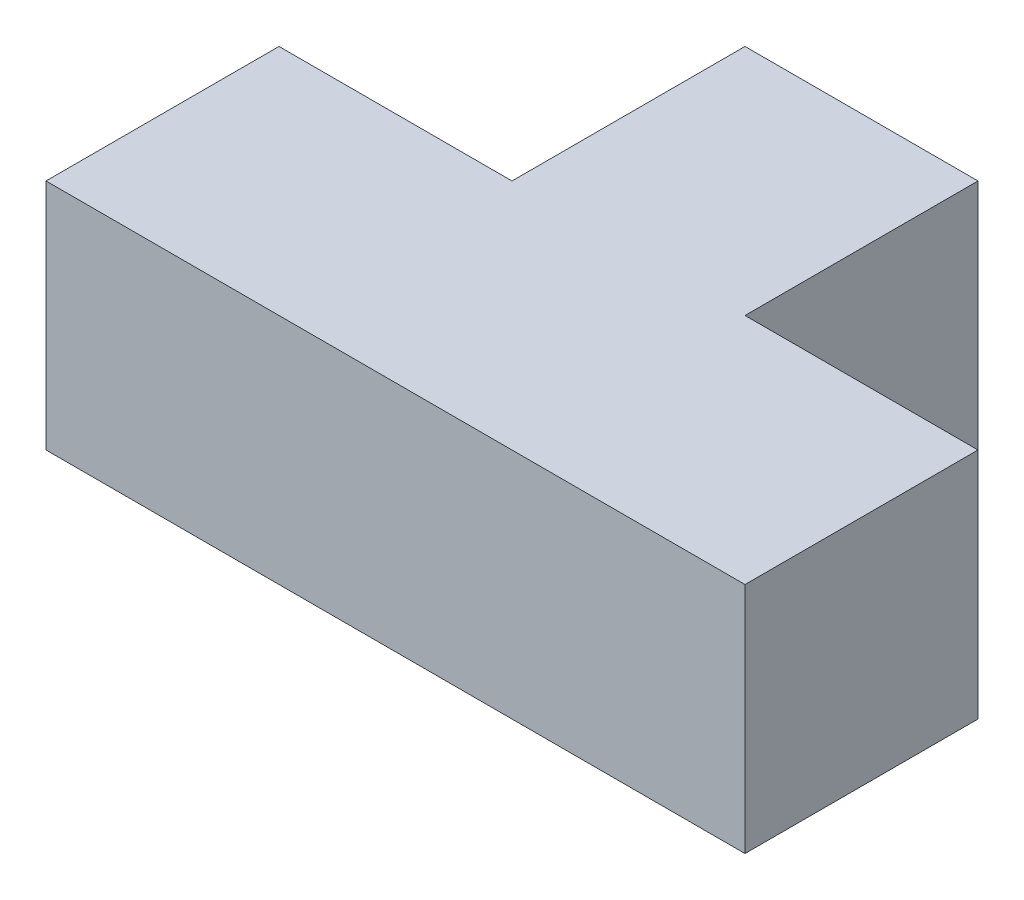
SolidWorks part; units mm, degrees
material "Oak"
ref_plane "Front Plane" through (0, 0, 0) normal (0, 0, 1) x (1, 0, 0)
ref_plane "Top Plane" through (0, 0, 0) normal (0, 1, 0) x (1, 0, 0)
ref_plane "Right Plane" through (0, 0, 0) normal (1, 0, 0) x (0, 0, -1)
sketch "Sketch1" plane through (0, 0, 0) normal (0, 1, 0) x (1, 0, 0)
  line L0 (-30, 0) -> (60, 0)
  line L1 (-30, 30) -> (-30, 0)
  line L2 (-30, 30) -> (0, 30)
  line L3 (0, 30) -> (0, 60)
  line L4 (0, 60) -> (30, 60)
  line L5 (30, 60) -> (30, 30)
  line L6 (30, 30) -> (60, 30)
  line L7 (60, 30) -> (60, 0)
  dimension "D1" = 30
  dimension "D2" = 30
  dimension "D3" = 30
  dimension "D4" = 30
  dimension "D5" = 90
  dimension "D6" = 60
extrude "Boss-Extrude1" add sketch "Sketch1" along normal blind 30
